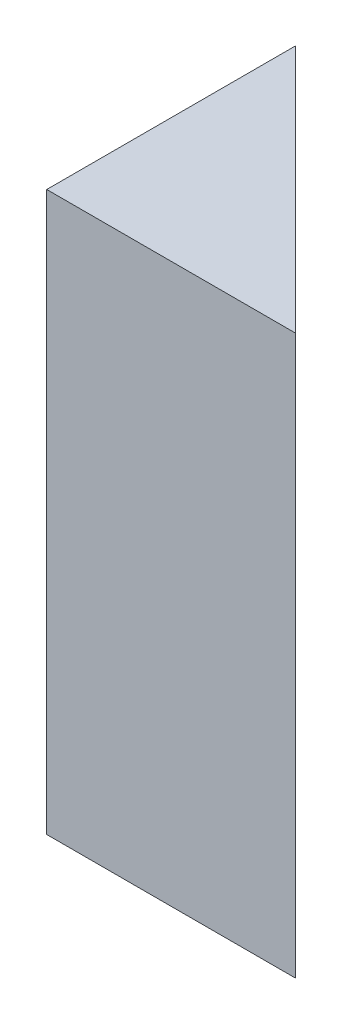
SolidWorks part; units mm, degrees
ref_plane "Front Plane" through (0, 0, 0) normal (0, 0, 1) x (1, 0, 0)
ref_plane "Top Plane" through (0, 0, 0) normal (0, 1, 0) x (1, 0, 0)
ref_plane "Right Plane" through (0, 0, 0) normal (1, 0, 0) x (0, 0, -1)
sketch "Sketch1" plane through (0, 0, 0) normal (0, 1, 0) x (1, 0, 0)
  line L0 (0, 0) -> (20, 0)
  line L1 (20, 0) -> (0, 20)
  line L2 (0, 20) -> (0, 0)
  point P4 (0, 0)
  point P6 (0, 0)
  dimension "D1" = 20
  dimension "D2" = 20
extrude "Boss-Extrude1" add sketch "Sketch1" along normal blind 44.958
